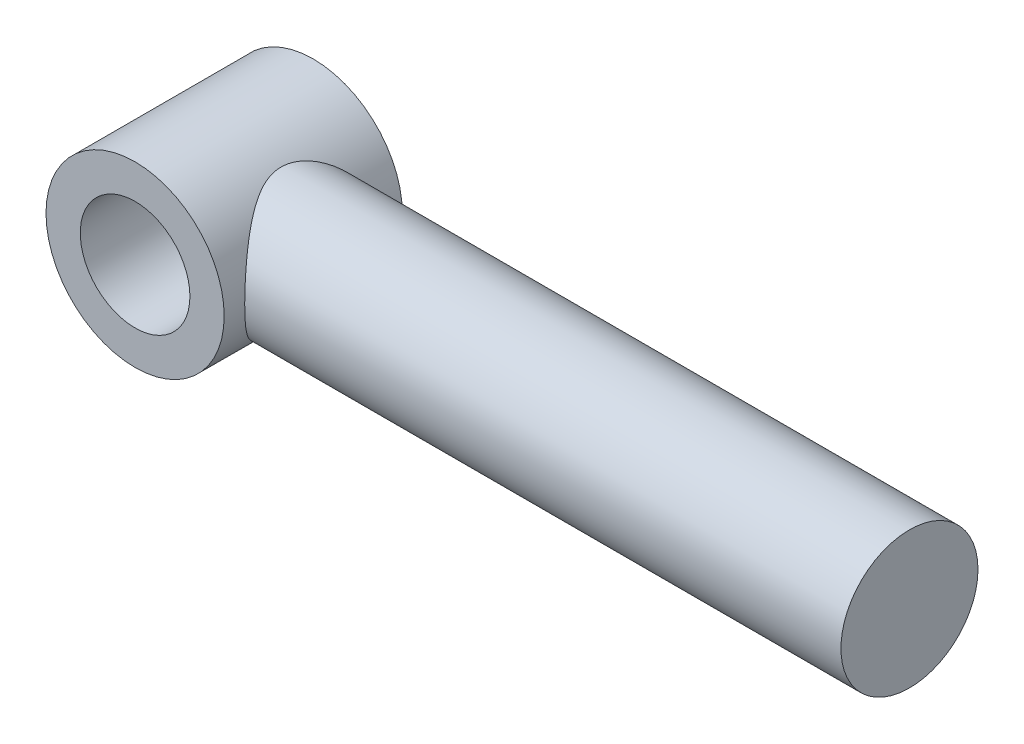
SolidWorks part; units mm, degrees
material "Q235"
ref_plane "前视基准面" through (0, 0, 0) normal (0, 0, 1) x (1, 0, 0)
ref_plane "上视基准面" through (0, 0, 0) normal (0, 1, 0) x (1, 0, 0)
ref_plane "右视基准面" through (0, 0, 0) normal (1, 0, 0) x (0, 0, -1)
sketch "草图1" plane through (0, 0, 0) normal (0, 0, 1) x (1, 0, 0)
  circle A0 centre (0, 0) radius 32.5
  circle A1 centre (0, 0) radius 20
  dimension "D1" = 40
  dimension "D2" = 65
extrude "凸台-拉伸1" add sketch "草图1" along normal mid plane 65
ref_plane "基准面1" through (250, 0, 0) normal (1, 0, 0) x (0, 0, -1)
sketch "草图2" plane through (250, 0, 0) normal (1, 0, 0) x (0, 0, -1)
  circle A0 centre (0, 0) radius 25
  dimension "D1" = 50
extrude "凸台-拉伸2" add sketch "草图2" against normal up to surface (217.5 mm away) up to face at (32.5, 0, 32.5)
